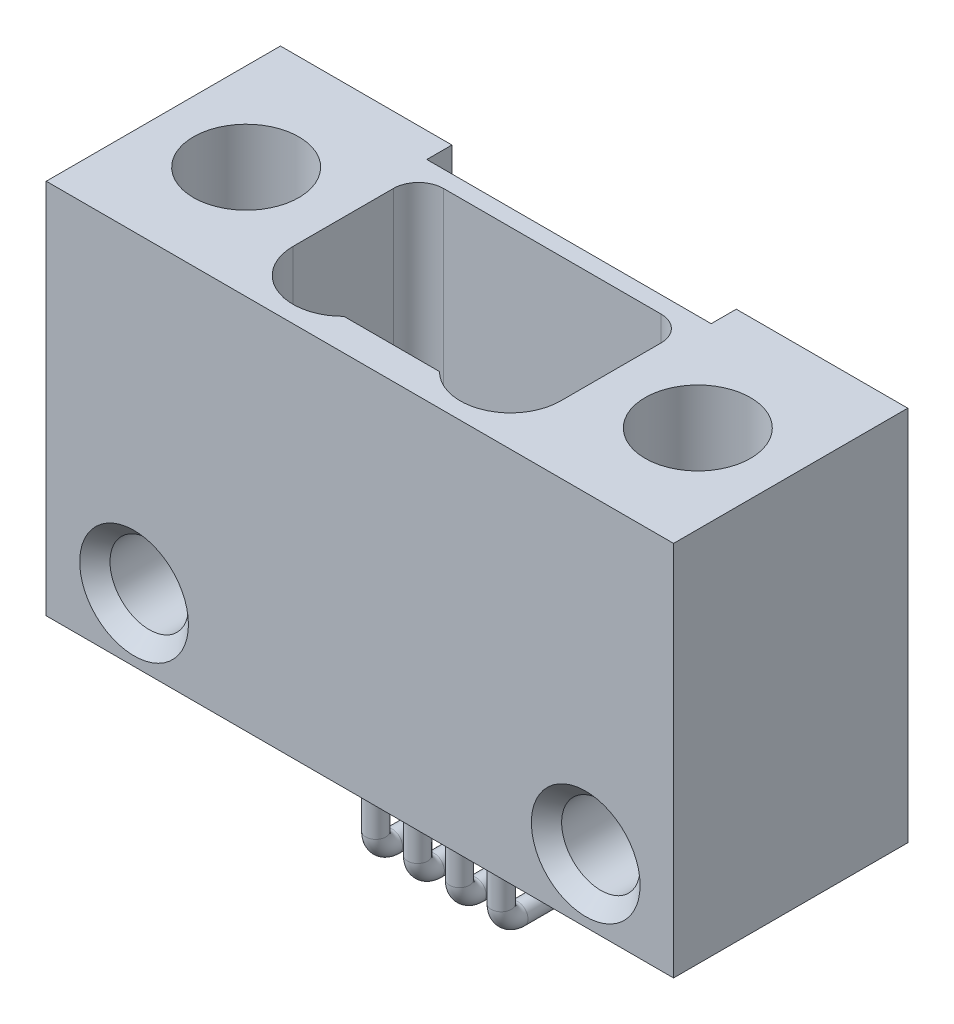
SolidWorks part; units mm, degrees
ref_plane "Front Plane" through (0, 0, 0) normal (0, 0, 1) x (1, 0, 0)
ref_plane "Top Plane" through (0, 0, 0) normal (0, 1, 0) x (1, 0, 0)
ref_plane "Right Plane" through (0, 0, 0) normal (1, 0, 0) x (0, 0, -1)
sketch "Sketch2" plane through (0, 0, 0) normal (0, 1, 0) x (1, 0, 0)
  line L0 (-2.159, 1.8542) -> (-2.159, 1.4732)
  line L1 (-2.159, 1.4732) -> (2.159, 1.4732)
  line L2 (2.159, 1.4732) -> (2.159, 1.8542)
  line L4 (2.159, 1.8542) -> (4.7625, 1.8542)
  line L5 (-4.7625, -1.7018) -> (4.7625, -1.7018)
  line L6 (4.7625, 1.8542) -> (4.7625, -1.7018)
  line L7 (-4.7625, 1.8542) -> (-2.159, 1.8542)
  line L8 (-4.7625, 1.8542) -> (-4.7625, -1.7018)
  point P4 (0, -1.7018)
  point P7 (0, 1.4732)
  dimension "D1" = 1.8542
  dimension "D2" = 3.556
  dimension "D3" = 9.525
  dimension "D4" = 1.7018
  dimension "D5" = 1.4732
  dimension "D6" = 4.318
extrude "Boss-Extrude2" add sketch "Sketch2" along normal blind 5.715
sketch "Sketch7" plane through (0, 0, 0) normal (0, 1, 0) x (1, 0, 0)
  line L0 (-1.651, 1.2192) -> (1.651, 1.2192)
  line L1 (2.032, 0.8382) -> (2.032, -0.6858)
  line L2 (0.7258, -1.2192) -> (-0.7258, -1.2192)
  line L3 (0, -1.8912) -> (0, -4.5956) construction
  line L5 (-2.032, 0.8382) -> (-2.032, -0.6858)
  arc A0 (2.032, -0.6858) -> (0.7258, -1.2192) centre (1.27, -0.6858) cw
  arc A1 (1.651, 1.2192) -> (2.032, 0.8382) centre (1.651, 0.8382) cw
  arc A2 (-1.651, 1.2192) -> (-2.032, 0.8382) centre (-1.651, 0.8382) ccw
  arc A3 (-2.032, -0.6858) -> (-0.7258, -1.2192) centre (-1.27, -0.6858) ccw
  dimension "D1" = 0.381
  dimension "D6" = 0.762
  dimension "D2" = 4.064
  dimension "D3" = 1.2192
  dimension "D4" = 2.4384
  dimension "D5" = 2.667
sketch "Sketch4" plane through (0, 0, 0) normal (0, 1, 0) x (1, 0, 0)
  circle A4 centre (1.27, 0.508) radius 0.1524
  circle A5 centre (0.635, 0.508) radius 0.1524
  circle A6 centre (0, 0.508) radius 0.1524
  circle A7 centre (-0.635, 0.508) radius 0.1524
  circle A8 centre (-1.27, 0.508) radius 0.1524
  dimension "D2" = 0.3048
  dimension "D7" = 0.508
  dimension "D8" = 0.635
  dimension "D9" = 0.635
  dimension "D10" = 0.635
  dimension "D11" = 0.635
sketch "Sketch3" plane through (0, 0, 0) normal (1, 0, 0) x (0, 0, -1)
  line L0 (0.508, 0) -> (0.508, -0.254)
  line L1 (0.762, -0.508) -> (1.4224, -0.508)
  line L2 (1.6764, -0.762) -> (1.6764, -1.2446)
  arc A0 (1.4224, -0.508) -> (1.6764, -0.762) centre (1.4224, -0.762) cw
  arc A1 (0.508, -0.254) -> (0.762, -0.508) centre (0.762, -0.254) ccw
  point P8 (0.508, -0.508)
  dimension "D1" = 0.508
  dimension "D4" = 0.254
  dimension "D2" = 1.1684
  dimension "D3" = 1.2446
extrude "Cut-Extrude1" cut sketch "Sketch7" along normal through all from offset 1.016
sweep "Sweep1" add profiles "Sketch4" path "Sketch3"
sketch "Sketch8" plane through (0, 5.715, 0) normal (0, 1, 0) x (1, 0, 0)
  circle A0 centre (3.429, 0) radius 0.8001
  circle A1 centre (-3.429, 0) radius 0.8001
  dimension "D1" = 6.858
  dimension "D2" = 1.6002
  dimension "D3" = 3.429
extrude "Cut-Extrude2" cut sketch "Sketch8" against normal blind 2.54
sketch "Sketch9" plane through (0, 0, 0) normal (0, 0, 1) x (1, 0, 0)
  circle A0 centre (3.429, 0.9652) radius 0.508
  circle A1 centre (-3.429, 0.9652) radius 0.508
  dimension "D2" = 3.429
  dimension "D3" = 3.429
  dimension "D4" = 1.016
  dimension "D1" = 0.9652
extrude "Cut-Extrude3" [suppressed] cut sketch "Sketch9" against normal through all and the other way through all
hole_wizard "#0-80 Tapped Hole1" positions "Sketch11" profile "Sketch10" tap size "#0-80" standard "Ansi Inch" end condition through all
sketch "Sketch11" plane through (0, 0, 1.7018) normal (0, 0, 1) x (1, 0, 0)
  line L0 (0, 1.951) -> (0, 4.0715) construction
  point P0 (3.429, 0.9652)
  point P1 (-3.429, 0.9652)
  dimension "D1" = 6.858
  dimension "D2" = 0.9652
sketch "Sketch10" plane through (3.429, 0.9652, 1.7018) normal (1, 0, 0) x (0, -1, 0)
  line L0 (0, 0) -> (0, 3.556)
  line L1 (0, 3.556) -> (0.8255, 3.556)
  line L2 (0.5956, 3.3261) -> (0.5956, 0.2299)
  line L3 (0.5956, 0.2299) -> (0.8255, 0)
  line L5 (0.8255, 0) -> (0, 0)
  line L6 (-0.5956, 0.2299) -> (-0.8255, 0) construction
  line L7 (0.8255, 3.556) -> (0.5956, 3.3261)
  line L8 (-0.8255, 3.556) -> (-0.5956, 3.3261) construction
  line L11 (0, -6.35) -> (0, 107.95) construction
  dimension "Thread Major Dia." = 1.1913
  dimension "Thru Tap Drill Depth" = 3.556
  dimension "Near C'Sink Dia." = 1.651
  dimension "Near C'Sink Angle" = 90
  dimension "Far C'Sink Dia." = 1.651
  dimension "Far C'Sink Angle" = 90
sketch "Sketch12" plane through (0, 0, 0) normal (0, 1, 0) x (1, 0, 0)
  circle A0 centre (0.9525, -0.508) radius 0.1524
  circle A1 centre (0.3175, -0.508) radius 0.1524
  circle A2 centre (-0.3175, -0.508) radius 0.1524
  circle A3 centre (-0.9525, -0.508) radius 0.1524
  dimension "D1" = 0.3048
  dimension "D2" = 0.635
  dimension "D3" = 0.635
  dimension "D4" = 0.635
  dimension "D5" = 0.3175
  dimension "D6" = 0.508
sketch "Sketch13" plane through (0, 0, 0) normal (1, 0, 0) x (0, 0, -1)
  line L0 (-0.508, 0) -> (-0.508, -1.524)
  line L1 (-0.254, -1.778) -> (1.4224, -1.778)
  line L2 (1.6764, -2.032) -> (1.6764, -2.5146)
  arc A0 (1.4224, -1.778) -> (1.6764, -2.032) centre (1.4224, -2.032) cw
  arc A1 (-0.508, -1.524) -> (-0.254, -1.778) centre (-0.254, -1.524) ccw
  dimension "D2" = 0.254
  dimension "D1" = 2.5146
  dimension "D3" = 1.778
sweep "Sweep2" add profiles "Sketch12" path "Sketch13"
sketch "Sketch14" plane through (0, 5.715, 0) normal (0, 1, 0) x (1, 0, 0)
  line L0 (0, 2.1082) -> (0, 3.4167) construction
  line L1 (-7.4295, 2.1082) -> (7.4295, 2.1082)
  line L2 (-7.4295, 2.1082) -> (-7.4295, -2.0828)
  line L3 (-7.4295, -2.0828) -> (7.4295, -2.0828)
  line L4 (7.4295, 2.1082) -> (7.4295, -2.0828)
  line L6 (-4.7625, -1.7018) -> (4.7625, -1.7018) construction
  line L10 (2.032, -0.6858) -> (2.032, 0.8382)
  line L11 (1.651, 1.2192) -> (-1.651, 1.2192)
  line L12 (-2.032, 0.8382) -> (-2.032, -0.6858)
  line L13 (-0.7258, -1.2192) -> (0.7258, -1.2192)
  line L14 (2.032, -0.6858) -> (2.032, 0.8382)
  line L15 (1.651, 1.2192) -> (-1.651, 1.2192)
  line L16 (-2.032, 0.8382) -> (-2.032, -0.6858)
  line L17 (-0.7258, -1.2192) -> (0.7258, -1.2192)
  circle A0 centre (6.096, 0.0254) radius 0.8255
  circle A1 centre (-6.096, 0.0254) radius 0.8255
  circle A2 centre (-3.429, 0) radius 0.8001 construction
  circle A3 centre (3.429, 0) radius 0.8001 construction
  circle A4 centre (-3.429, 0) radius 0.8001
  circle A5 centre (3.429, 0) radius 0.8001
  arc A6 (0.7258, -1.2192) -> (2.032, -0.6858) centre (1.27, -0.6858) ccw
  arc A7 (2.032, 0.8382) -> (1.651, 1.2192) centre (1.651, 0.8382) ccw
  arc A8 (-1.651, 1.2192) -> (-2.032, 0.8382) centre (-1.651, 0.8382) ccw
  arc A9 (-2.032, -0.6858) -> (-0.7258, -1.2192) centre (-1.27, -0.6858) ccw
  arc A10 (0.7258, -1.2192) -> (2.032, -0.6858) centre (1.27, -0.6858) ccw
  arc A11 (2.032, 0.8382) -> (1.651, 1.2192) centre (1.651, 0.8382) ccw
  arc A12 (-1.651, 1.2192) -> (-2.032, 0.8382) centre (-1.651, 0.8382) ccw
  arc A13 (-2.032, -0.6858) -> (-0.7258, -1.2192) centre (-1.27, -0.6858) ccw
  dimension "D1" = 1.651
  dimension "D5" = 12.192
  dimension "D2" = 14.859
  dimension "D3" = 4.191
  dimension "D4" = 0.381
  dimension "D6" = 1.7272
  dimension "D7" = 0
extrude "Boss-Extrude3" [suppressed] add sketch "Sketch14" against normal blind 1.6002
